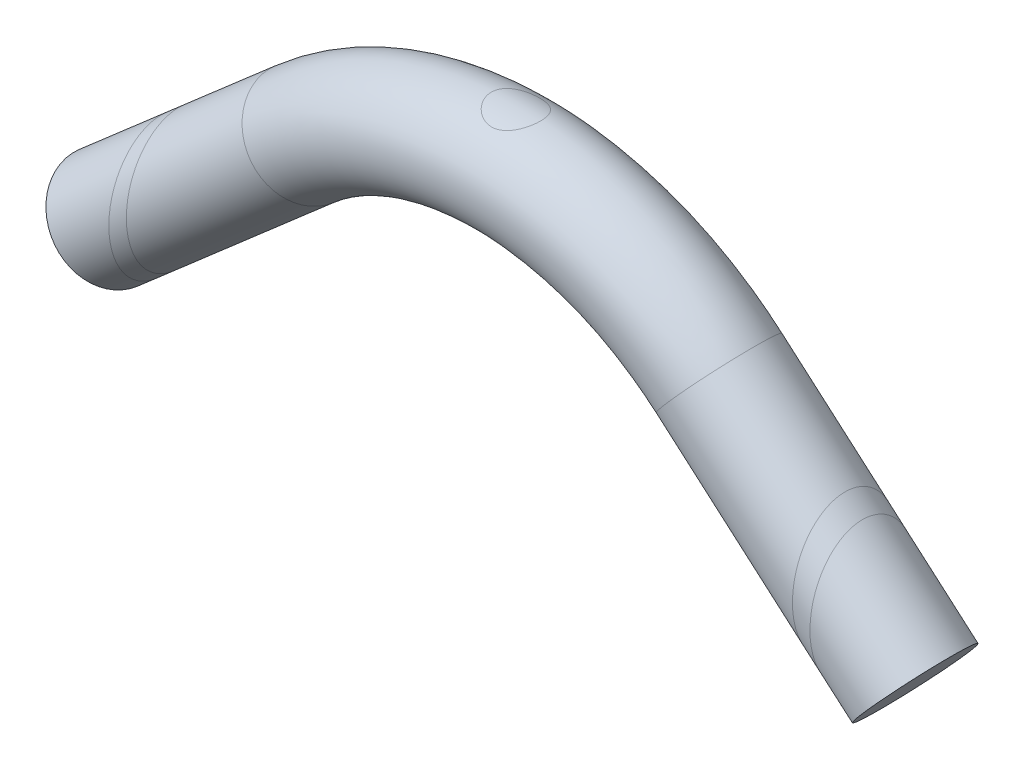
SolidWorks part; units mm, degrees
ref_plane "Front Plane" through (0, 0, 0) normal (0, 0, 1) x (1, 0, 0)
ref_plane "Top Plane" through (0, 0, 0) normal (0, 1, 0) x (1, 0, 0)
ref_plane "Right Plane" through (0, 0, 0) normal (1, 0, 0) x (0, 0, -1)
sketch "Sketch1" plane through (0, 0, 0) normal (0, 0, 1) x (1, 0, 0)
  line L0 (0, 0) -> (230, 0) construction
  line L1 (115, 0) -> (115, 70) construction
  line L2 (115, 70) -> (115, 100) construction
  line L3 (0, 0) -> (55.9439, 48.6469)
  line L4 (230, 0) -> (174.0561, 48.6469)
  arc A0 (174.0561, 48.6469) -> (55.9439, 48.6469) centre (115, -19.2676) ccw
  point P9 (115, 70.7324)
  dimension "D2" = 70
  dimension "D4" = 90
  dimension "D1" = 230
  dimension "D3" = 30
ref_plane "Plane1" through (115, 0, 0) normal (1, 0, 0) x (0, 0, -1)
sketch "Sketch3" plane through (115, 0, 0) normal (1, 0, 0) x (0, 0, -1)
  circle A0 centre (0, 70.7324) radius 15
sweep "Sweep1" add profiles "Sketch3" path "Sketch1"
mirror "Mirror1" about plane through (115, 0, 0) normal (1, 0, 0) of "Sweep1"
sketch "Sketch4" plane through (0, 0, 0) normal (0, 1, 0) x (1, 0, 0)
  circle A0 centre (116.1146, 0) radius 7
split line "Split Line4"
sketch "Sketch5" plane through (0, 0, 0) normal (0, 0, 1) x (1, 0, 0)
  line L0 (20, 103.8768) -> (20, -36.7986)
  line L1 (15, -36.7986) -> (15, 103.8768)
  line L2 (115, 0) -> (115, 70) construction
  line L3 (115, 0) -> (115, 107.9916) construction
  line L4 (0, 0) -> (230, 0) construction
  line L5 (215, -36.7986) -> (215, 103.8768)
  line L6 (210, 103.8768) -> (210, -36.7986)
  dimension "D1" = 5
  dimension "D2" = 100
split line "Split Line5"
sketch3d "3DSketch1"
  line L0 (115, 70, 0) -> (115, 21.1591, -13.0869) construction
  line L1 (115, 70, 0) -> (115, 18.4553, 0) construction
  line L2 (115, 0, 0) -> (115, 70, 0) construction
  dimension "D1" = 15
